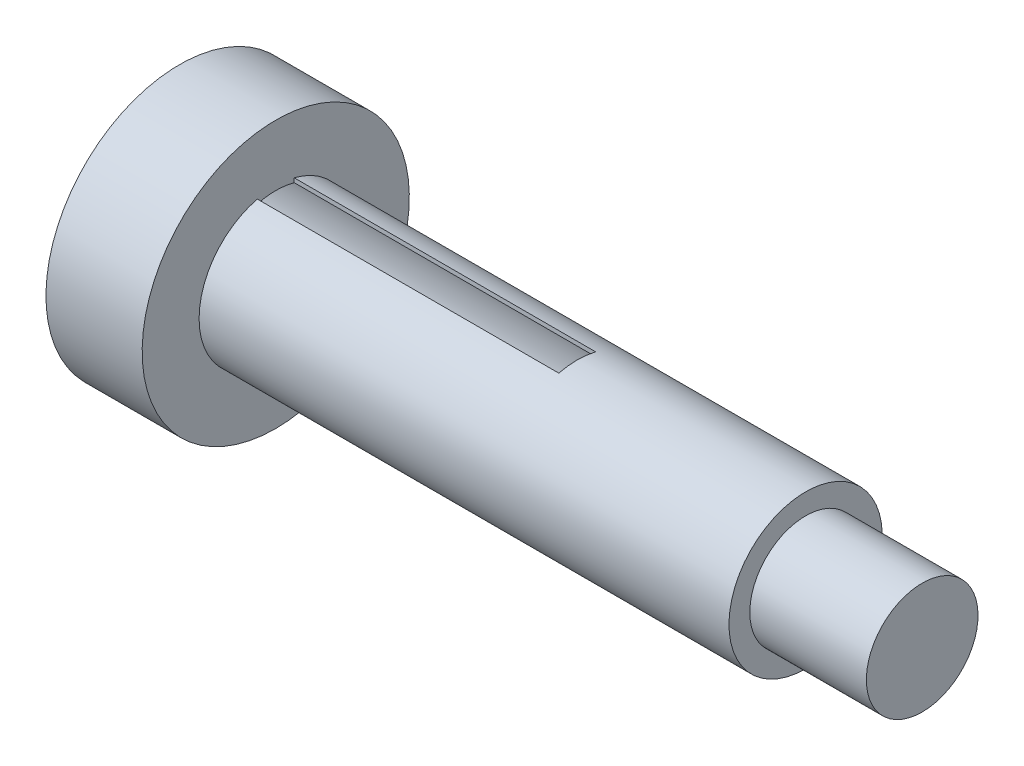
SolidWorks part; units mm, degrees
material "Plain Carbon Steel"
ref_plane "Front Plane" through (0, 0, 0) normal (0, 0, 1) x (1, 0, 0)
ref_plane "Top Plane" through (0, 0, 0) normal (0, 1, 0) x (1, 0, 0)
ref_plane "Right Plane" through (0, 0, 0) normal (1, 0, 0) x (0, 0, -1)
sketch "Sketch1" plane through (0, 0, 0) normal (0, 0, 1) x (1, 0, 0)
  line L0 (0, 0) -> (191.14, 0) construction
  line L1 (191.14, 0) -> (191.14, 14.37)
  line L2 (191.14, 14.37) -> (161.14, 14.37)
  line L3 (161.14, 14.37) -> (161.14, 19.73)
  line L4 (161.14, 19.73) -> (24.76, 19.73)
  line L5 (24.76, 19.73) -> (24.76, 34.38)
  line L6 (24.76, 34.38) -> (0, 34.38)
  line L7 (0, 34.38) -> (0, 18.68)
  line L8 (0, 18.68) -> (142.46, 18.68)
  line L9 (142.46, 18.68) -> (142.46, 0)
  line L10 (142.46, 0) -> (191.14, 0)
  dimension "D1" = 14.37
  dimension "D2" = 19.73
  dimension "D3" = 18.68
  dimension "D4" = 34.38
  dimension "D5" = 30
  dimension "D6" = 136.38
  dimension "D7" = 24.76
  dimension "D8" = 117.7
revolve "Revolve2" add sketch "Sketch1" angle 360 about L0
sketch "Sketch3" plane through (0, 0, 0) normal (0, 1, 0) x (1, 0, 0)
  line L0 (0, 0) -> (127.12, 0) construction
  line L1 (24.76, -34.38) -> (24.76, 34.38) construction
  line L2 (102.36, 4.745) -> (24.76, 4.745)
  line L3 (102.36, 4.745) -> (102.36, -4.745)
  line L4 (102.36, -4.745) -> (24.76, -4.745)
  line L5 (24.76, 4.745) -> (24.76, -4.745)
  line L6 (102.36, 4.745) -> (24.76, -4.745) construction
  line L7 (102.36, -4.745) -> (24.76, 4.745) construction
  point P3 (63.56, 0)
  dimension "D1" = 77.6
  dimension "D2" = 9.49
extrude "Cut-Extrude2" cut sketch "Sketch3" against normal through all and the other way through all
